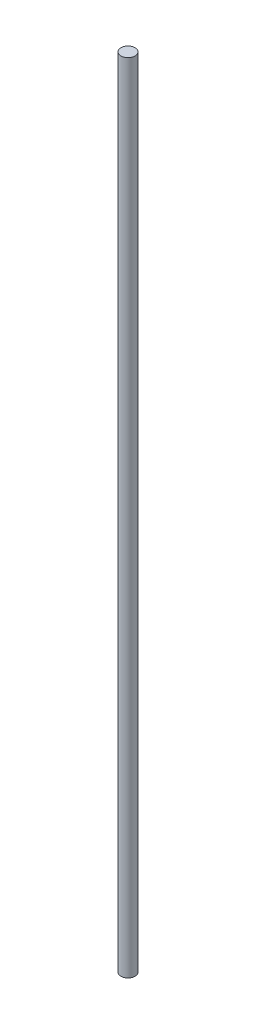
SolidWorks part; units mm, degrees
ref_plane "前视基准面" through (0, 0, 0) normal (0, 0, 1) x (1, 0, 0)
ref_plane "上视基准面" through (0, 0, 0) normal (0, 1, 0) x (1, 0, 0)
ref_plane "右视基准面" through (0, 0, 0) normal (1, 0, 0) x (0, 0, -1)
sketch "草图2" plane through (0, 0, 0) normal (0, 1, 0) x (1, 0, 0)
  circle A0 centre (0, 0) radius 5
  dimension "D1" = 10
extrude "凸台-拉伸1" add sketch "草图2" along normal blind 560
